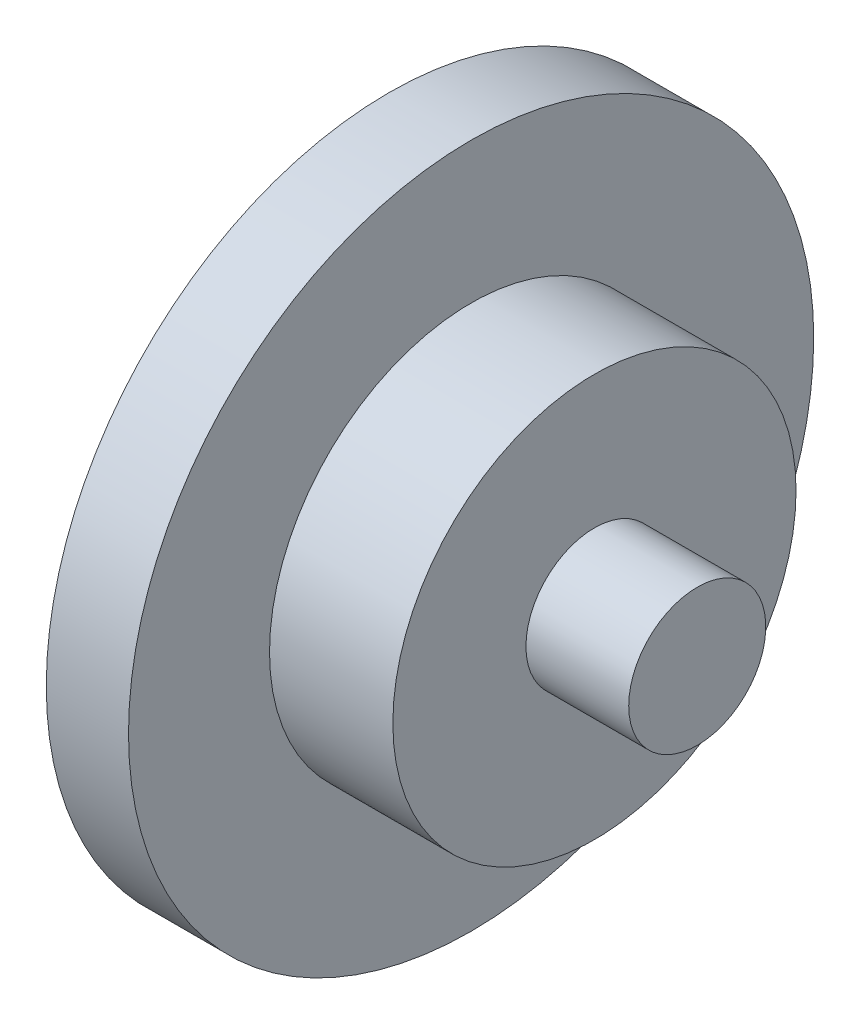
SolidWorks part; units mm, degrees
ref_plane "Front Plane" through (0, 0, 0) normal (0, 0, 1) x (1, 0, 0)
ref_plane "Top Plane" through (0, 0, 0) normal (0, 1, 0) x (1, 0, 0)
ref_plane "Right Plane" through (0, 0, 0) normal (1, 0, 0) x (0, 0, -1)
sketch "Sketch1" plane through (0, 0, 0) normal (0, 0, 1) x (1, 0, 0)
  line L0 (0, 50) -> (0, -50) construction
  line L1 (0, 10) -> (-15, 10)
  line L2 (-15, 10) -> (-15, 29.4212)
  line L3 (-15, 29.4212) -> (-33, 29.4212)
  line L4 (-33, 29.4212) -> (-33, 50)
  line L5 (-33, 50) -> (-45, 50)
  line L6 (-45, 50) -> (-45, 0)
  line L7 (-45, 0) -> (0, 0)
  line L8 (0, 0) -> (0, 10)
  dimension "D1" = 50
  dimension "D2" = 10
  dimension "D3" = 45
  dimension "D4" = 12
  dimension "D5" = 15
revolve "Revolve1" add sketch "Sketch1" angle 360 about L7
